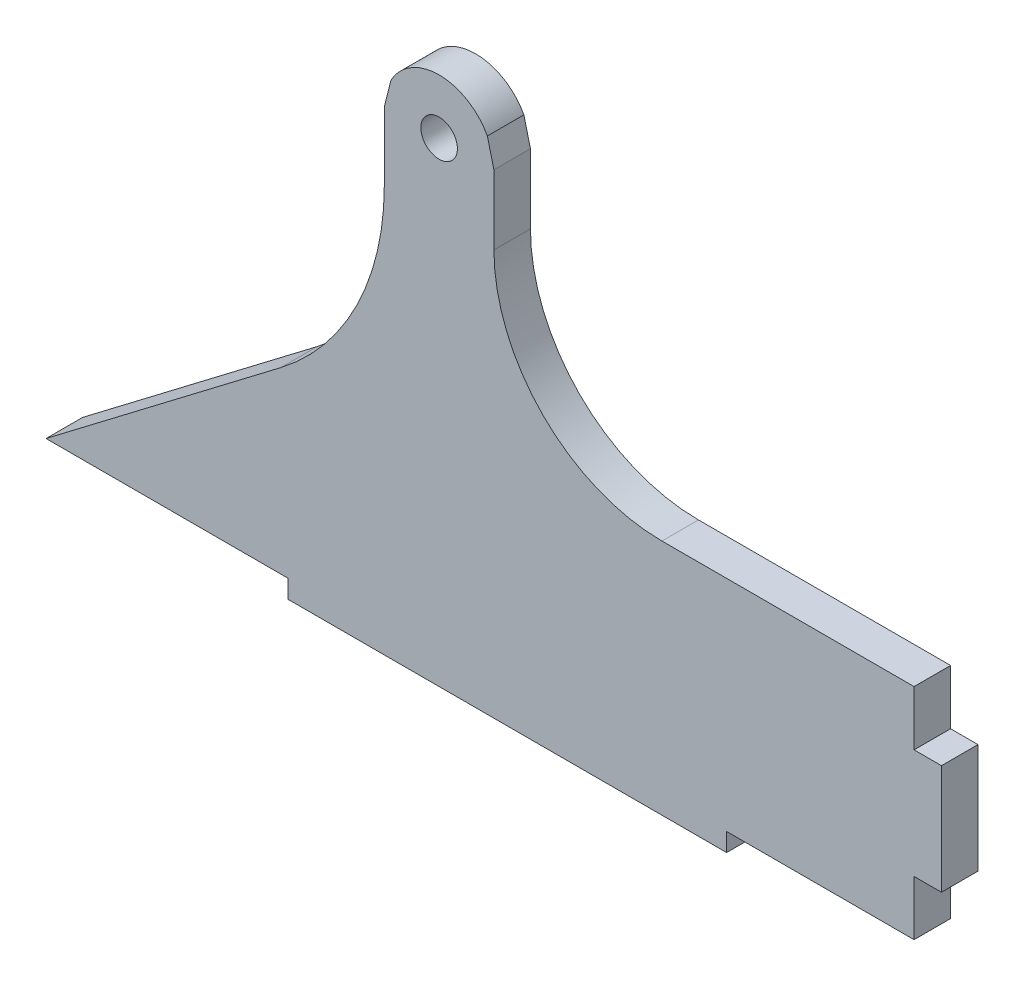
SolidWorks part; units mm, degrees
ref_plane "Front Plane" through (0, 0, 0) normal (0, 0, 1) x (1, 0, 0)
ref_plane "Top Plane" through (0, 0, 0) normal (0, 1, 0) x (1, 0, 0)
ref_plane "Right Plane" through (0, 0, 0) normal (1, 0, 0) x (0, 0, -1)
sketch "Sketch1" plane through (0, 0, 0) normal (0, 0, 1) x (1, 0, 0)
  line L0 (129.8035, 32.7787) -> (104.4035, 32.7787)
  line L1 (-171.9485, -43.4213) -> (-87.7475, -43.4213)
  line L4 (129.8035, -43.4213) -> (129.8035, -24.3713)
  line L5 (-171.9485, -43.4213) -> (129.8035, 32.7787) construction
  line L6 (-90.3867, 18.6912) -> (-171.9485, -43.4213)
  line L7 (-87.7475, -43.4213) -> (-87.7475, -49.7713)
  line L8 (-87.7475, -49.7713) -> (64.6525, -49.7713)
  line L9 (64.6525, -49.7713) -> (64.6525, -43.4213)
  line L16 (64.6525, -43.4213) -> (129.8035, -43.4213)
  line L17 (129.8035, 13.7287) -> (139.3285, 13.7287)
  line L18 (129.8035, 13.7287) -> (129.8035, 32.7787)
  line L19 (139.3285, -24.3713) -> (129.8035, -24.3713)
  line L20 (139.3285, 13.7287) -> (139.3285, -24.3713) construction
  line L21 (139.3285, 13.7287) -> (139.3285, -24.3713)
  line L23 (-16.2465, 115.3287) -> (-18.5281, 124.3689)
  line L24 (-61.2293, -49.7713) -> (-16.6946, -49.7713)
  line L27 (-52.0648, 124.3689) -> (-54.3465, 115.3287)
  line L29 (104.4035, 32.7787) -> (44.0785, 32.7787)
  line L30 (-16.2465, 91.1987) -> (-16.2465, 115.3287)
  line L31 (44.0785, 32.7787) -> (42.1735, 32.7787)
  line L32 (-54.3465, 115.3287) -> (-54.3465, 91.4383)
  line L33 (-54.3465, 91.4383) -> (-54.3465, 115.3287)
  line L34 (-16.2465, 115.3287) -> (-16.2465, 91.1987)
  line L36 (89.2905, 32.7787) -> (51.1905, 32.7787)
  line L37 (89.2905, 46.5975) -> (89.2905, 59.3139)
  circle A1 centre (-35.2965, 115.3287) radius 6.35
  arc A3 (-16.2465, 115.3287) -> (-54.3465, 115.3287) centre (-35.2965, 115.3287) ccw
  arc A5 (42.1735, 32.7787) -> (-16.2465, 91.1987) centre (42.1735, 91.1987) cw
  arc A6 (-54.3465, 91.4383) -> (-90.3867, 18.6912) centre (-145.7865, 91.4383) cw
  point P0 (0, 0)
  dimension "D13" = 165.1
  dimension "D14" = 12.7
  dimension "D15" = 165.1
  dimension "D16" = 58.42
  dimension "D7" = 91.44
  dimension "D2" = 301.752
  dimension "D3" = 76.2
  dimension "D4" = 6.35
  dimension "D5" = 152.4
  dimension "D6" = 38.1
  dimension "D8" = 50.038
  dimension "2.565" = 65.151
  dimension "D9" = 9.525
  dimension "D10" = 165.1
  dimension "D11" = 19.05
  dimension "D12" = 38.1
  dimension "D18" = 0
extrude "Boss-Extrude1" add sketch "Sketch1" along normal blind 12.7
